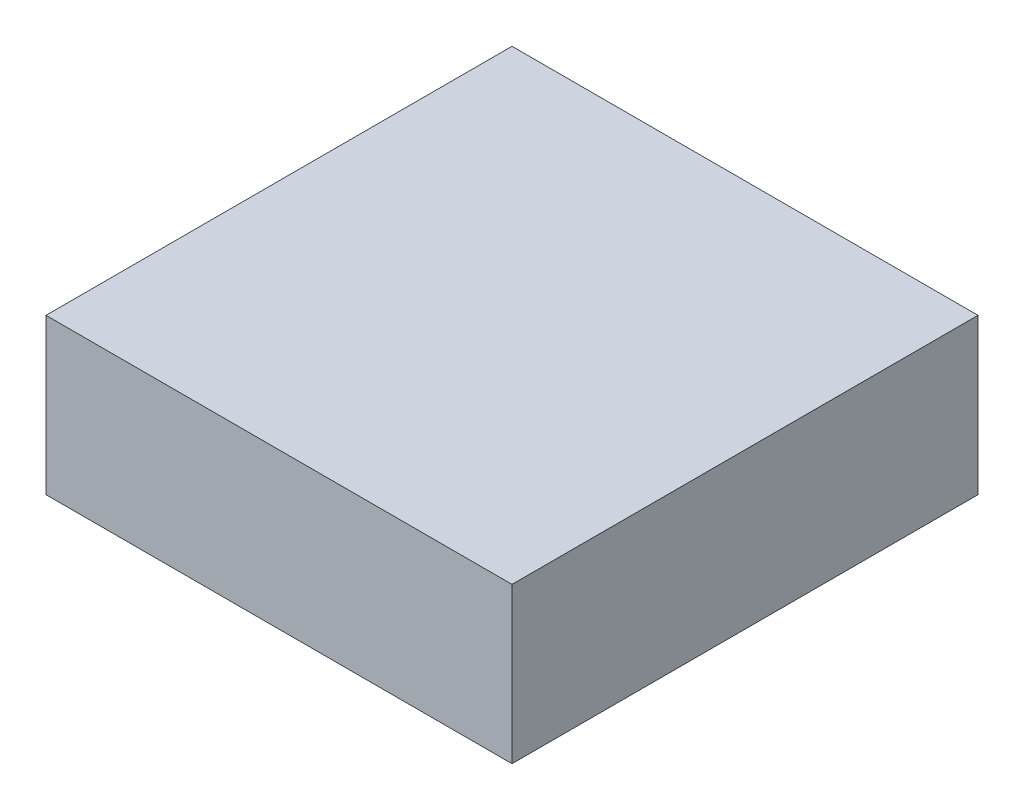
SolidWorks part; units mm, degrees
ref_plane "Front Plane" through (0, 0, 0) normal (0, 0, 1) x (1, 0, 0)
ref_plane "Top Plane" through (0, 0, 0) normal (0, 1, 0) x (1, 0, 0)
ref_plane "Right Plane" through (0, 0, 0) normal (1, 0, 0) x (0, 0, -1)
sketch "Sketch1" plane through (0, 0, 0) normal (0, 1, 0) x (1, 0, 0)
  line L1 (0, 0) -> (3, 0)
  line L2 (0, 0) -> (0, -3)
  line L3 (0, -3) -> (3, -3)
  line L4 (3, 0) -> (3, -3)
  dimension "D1" = 3
  dimension "D2" = 3
extrude "Boss-Extrude1" add sketch "Sketch1" along normal blind 1
